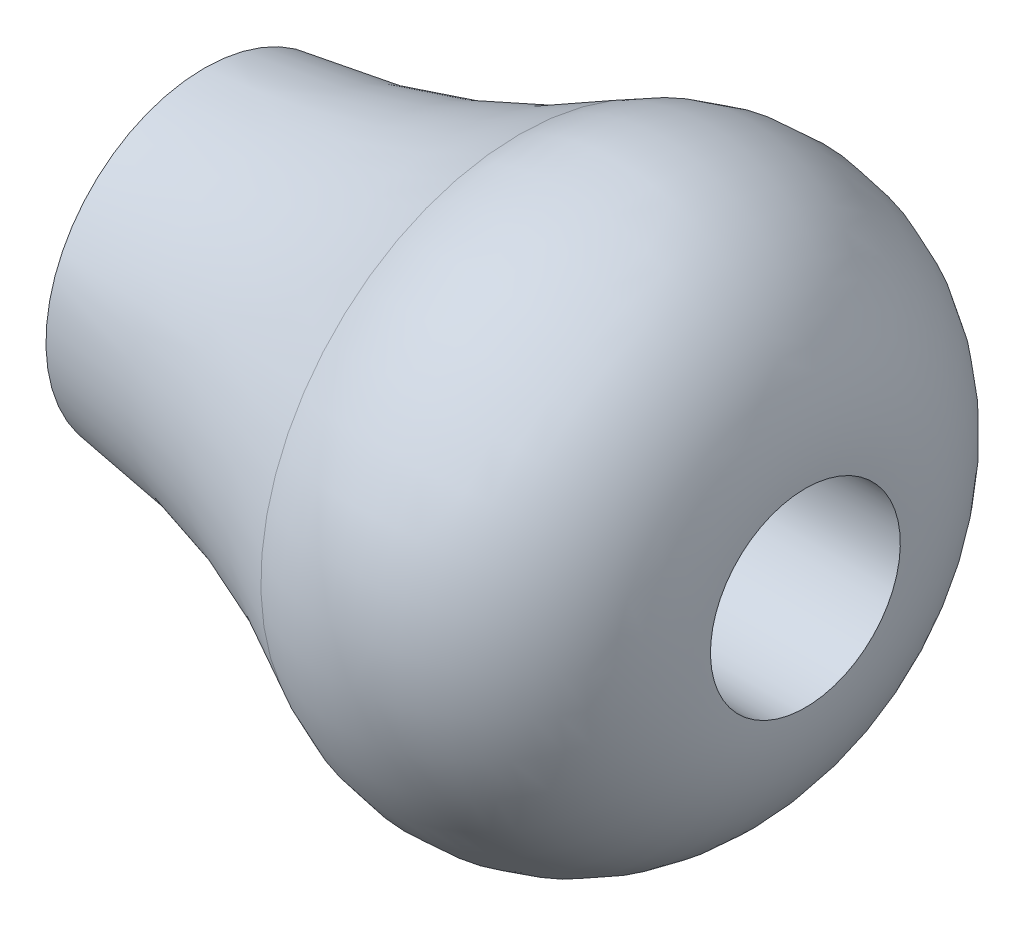
SolidWorks part; units mm, degrees
ref_plane "Front" through (0, 0, 0) normal (0, 0, 1) x (1, 0, 0)
ref_plane "Top" through (0, 0, 0) normal (0, 1, 0) x (1, 0, 0)
ref_plane "Right" through (0, 0, 0) normal (1, 0, 0) x (0, 0, -1)
sketch "Sketch1" plane through (0, 0, 0) normal (0, 0, 1) x (1, 0, 0)
  line L0 (0, 1.75) -> (5, 1.75)
  line L1 (5, 1.75) -> (5, 3)
  line L2 (5, 3) -> (19, 3)
  line L3 (0, 5) -> (0, 1.75)
  line L4 (0, 0) -> (-2.1529, 0) construction
  line L5 (0, 5) -> (7.1364, 5.6244) construction
  line L6 (19, 3) -> (19, 5.3318) construction
  arc A0 (19, 3) -> (9.9674, 8.1772) centre (13, 3) ccw
  arc A1 (9.9674, 8.1772) -> (0, 5) centre (-2.0769, 28.7388) cw
  point P11 (0, 0)
  dimension "D1" = 3.5
  dimension "D2" = 6
  dimension "D3" = 5
  dimension "D4" = 14
  dimension "D5" = 18
  dimension "D6" = 5
  dimension "D7" = 10
revolve "Revolve1" add sketch "Sketch1" angle 360 about L4
